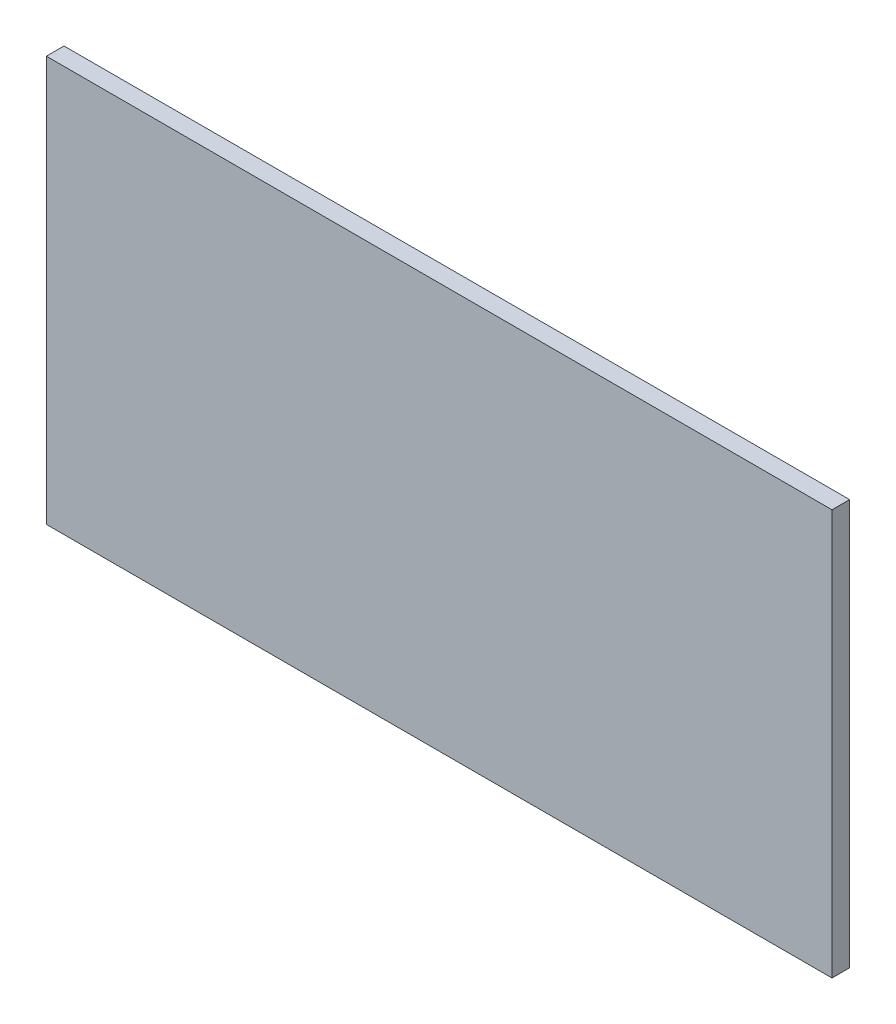
SolidWorks part; units mm, degrees
material "Q235A"
ref_plane "前视" through (0, 0, 0) normal (0, 0, 1) x (1, 0, 0)
ref_plane "上视" through (0, 0, 0) normal (0, 1, 0) x (1, 0, 0)
ref_plane "右视" through (0, 0, 0) normal (1, 0, 0) x (0, 0, -1)
sketch "草图1" plane through (0, 0, 0) normal (0, 0, 1) x (1, 0, 0)
  line L1 (356.5, -184) -> (-356.5, -184)
  line L2 (356.5, -184) -> (356.5, 184)
  line L3 (356.5, 184) -> (-356.5, 184)
  line L4 (-356.5, -184) -> (-356.5, 184)
  line L5 (356.5, -184) -> (-356.5, 184) construction
  line L6 (356.5, 184) -> (-356.5, -184) construction
  point P0 (0, 0)
  dimension "D1" = 368
  dimension "D2" = 713
extrude "凸台-拉伸1" add sketch "草图1" along normal blind 16
